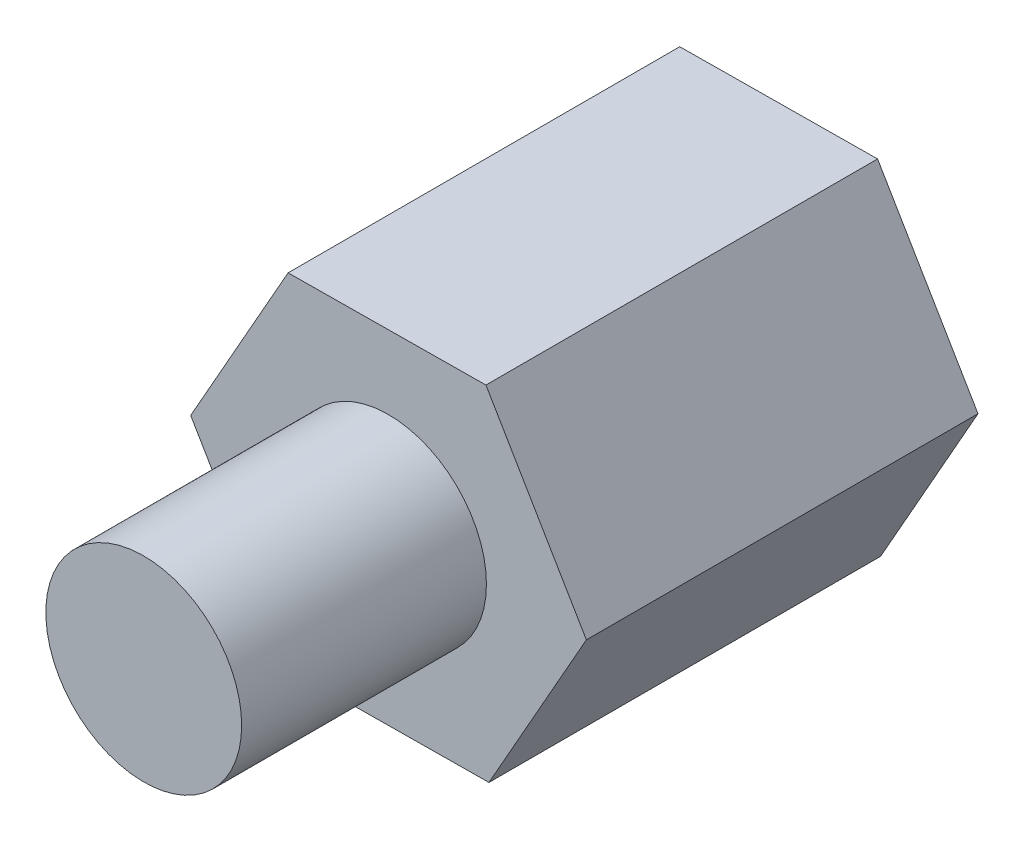
SolidWorks part; units mm, degrees
ref_plane "前视基准面" through (0, 0, 0) normal (0, 0, 1) x (1, 0, 0)
ref_plane "上视基准面" through (0, 0, 0) normal (0, 1, 0) x (1, 0, 0)
ref_plane "右视基准面" through (0, 0, 0) normal (1, 0, 0) x (0, 0, -1)
sketch "草图1" plane through (0, 0, 0) normal (0, 0, 1) x (1, 0, 0)
  line L1 (2.0515, -3.4821) -> (4.0413, 0.0356)
  line L2 (4.0413, 0.0356) -> (1.9898, 3.5177)
  line L3 (1.9898, 3.5177) -> (-2.0515, 3.4821)
  line L4 (-2.0515, 3.4821) -> (-4.0413, -0.0356)
  line L5 (-4.0413, -0.0356) -> (-1.9898, -3.5177)
  line L6 (-1.9898, -3.5177) -> (2.0515, -3.4821)
  circle A0 centre (0, 0) radius 3.5 construction
  circle A1 centre (0, 0) radius 2
extrude "凸台-拉伸1" add sketch "草图1" along normal blind 8
sketch "草图3" plane through (0, 0, 8) normal (0, 0, 1) x (1, 0, 0)
  circle A0 centre (0, 0) radius 2
extrude "凸台-拉伸2" add sketch "草图3" along normal blind 5 separate body
